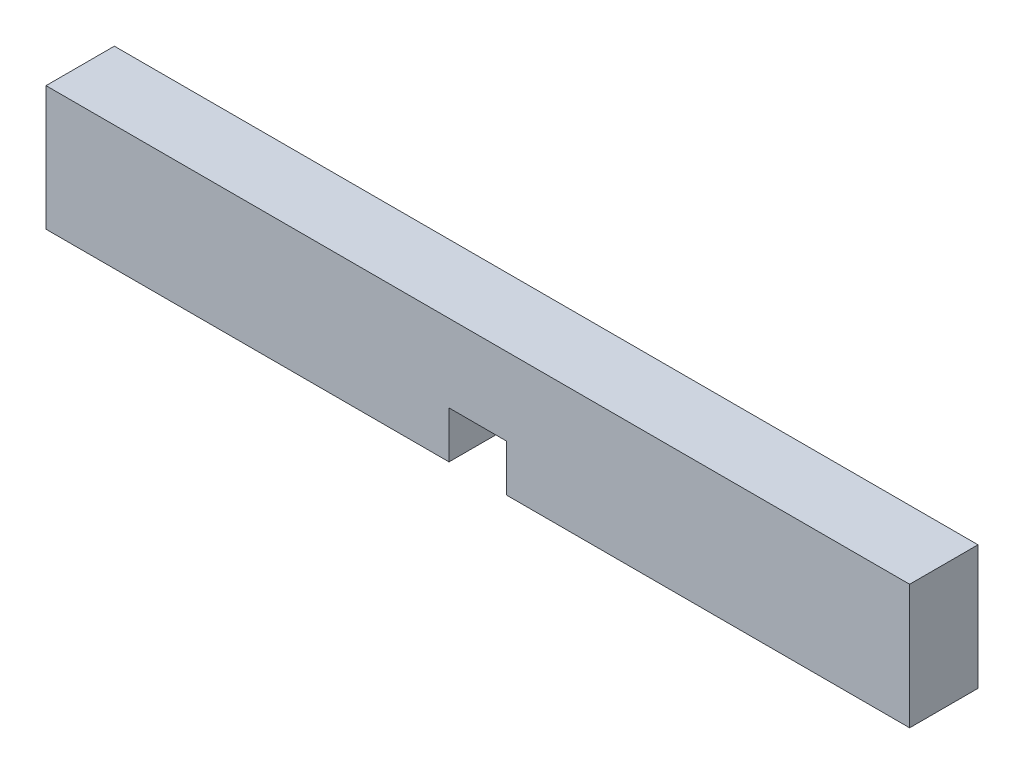
SolidWorks part; units mm, degrees
ref_plane "Alzado" through (0, 0, 0) normal (0, 0, 1) x (1, 0, 0)
ref_plane "Planta" through (0, 0, 0) normal (0, 1, 0) x (1, 0, 0)
ref_plane "Vista lateral" through (0, 0, 0) normal (1, 0, 0) x (0, 0, -1)
sketch "Croquis1" plane through (0, 0, 0) normal (0, 0, 1) x (1, 0, 0)
  line L1 (-30, -4.32) -> (30, -4.32)
  line L2 (-30, -4.32) -> (-30, 4.32)
  line L3 (-30, 4.32) -> (30, 4.32)
  line L4 (30, -4.32) -> (30, 4.32)
  line L5 (-30, -4.32) -> (30, 4.32) construction
  line L6 (-30, 4.32) -> (30, -4.32) construction
  line L11 (-2, -1.07) -> (2, -1.07)
  line L12 (-2, -1.07) -> (-2, -4.32)
  line L13 (-2, -4.32) -> (2, -4.32)
  line L14 (2, -1.07) -> (2, -4.32)
  line L15 (-2, -1.07) -> (2, -4.32) construction
  line L16 (-2, -4.32) -> (2, -1.07) construction
  point P0 (0, 0)
  point P6 (0, -4.32)
  point P7 (0, -2.695)
  point P12 (0, 0)
  dimension "D1" = 60
  dimension "D2" = 8.64
  dimension "D3" = 4
  dimension "D4" = 3.25
extrude "Saliente-Extruir1" add sketch "Croquis1" along normal mid plane 4.75 contours L11 L14 L1 L4 L3 L2 L12
